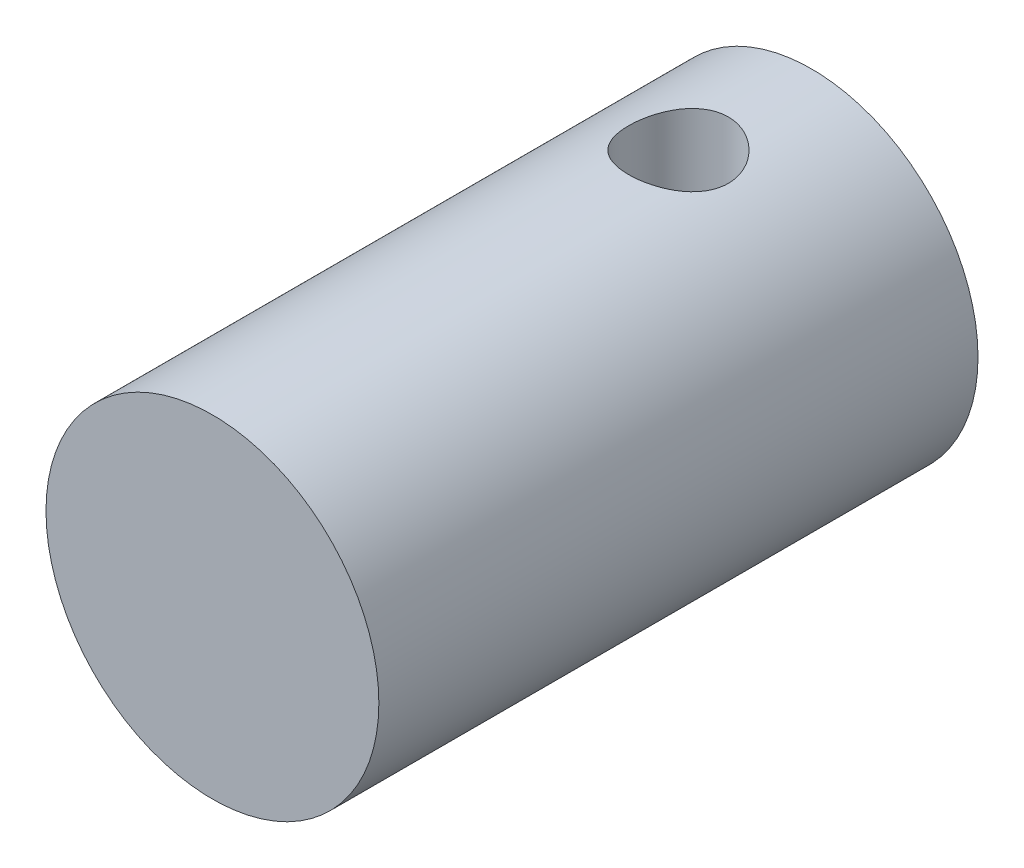
SolidWorks part; units mm, degrees
ref_plane "Front Plane" through (0, 0, 0) normal (0, 0, 1) x (1, 0, 0)
ref_plane "Top Plane" through (0, 0, 0) normal (0, 1, 0) x (1, 0, 0)
ref_plane "Right Plane" through (0, 0, 0) normal (1, 0, 0) x (0, 0, -1)
sketch "Sketch1" plane through (0, 0, 0) normal (0, 0, 1) x (1, 0, 0)
  circle A0 centre (-63.2013, 37.6957) radius 25
  dimension "D1" = 50
extrude "Boss-Extrude1" add sketch "Sketch1" along normal blind 90
sketch "Sketch2" plane through (0, 0, 0) normal (0, 1, 0) x (1, 0, 0)
  line L0 (-88.2013, -90) -> (-38.2013, -90) construction
  line L1 (-63.2013, -90) -> (-63.2013, -20) construction
  circle A0 centre (-63.2013, -20) radius 7.5
  point P0 (-63.2013, -90)
  dimension "D2" = 15
  dimension "D1" = 70
extrude "Cut-Extrude2" cut sketch "Sketch2" along normal blind 101
